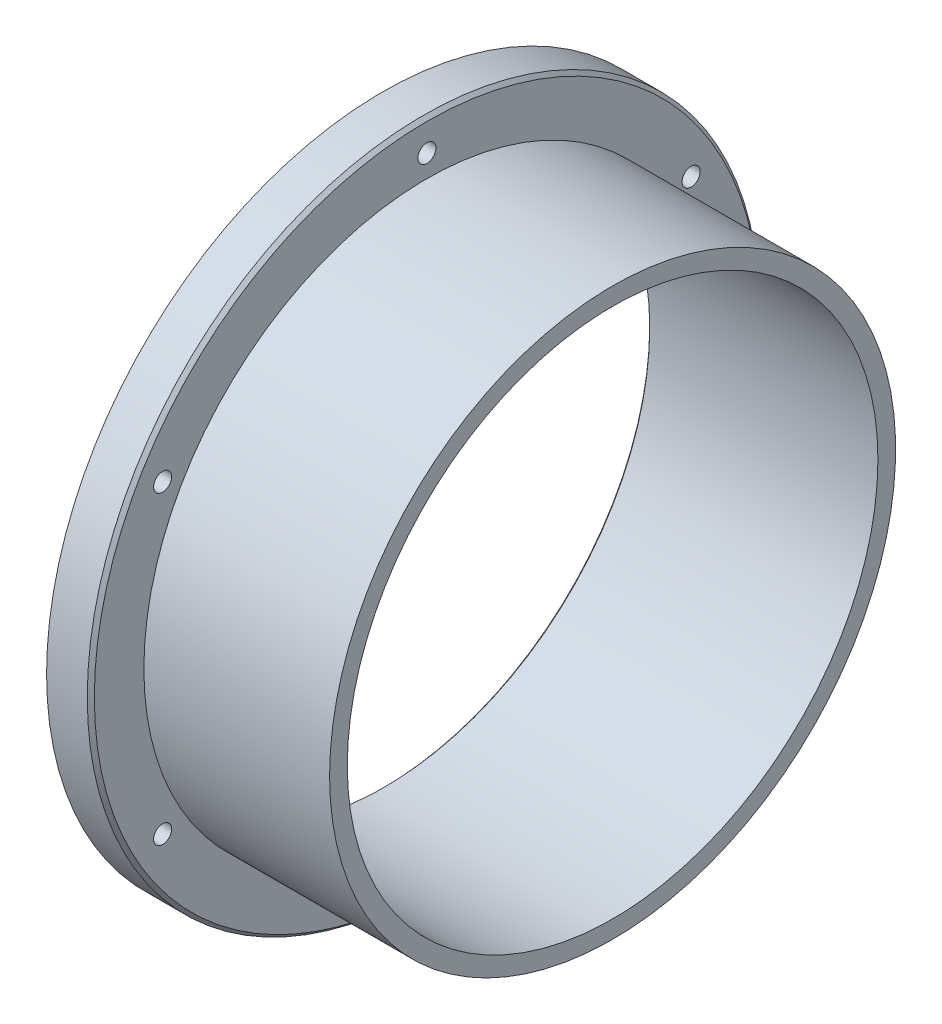
SolidWorks part; units mm, degrees
ref_plane "Спереди" through (0, 0, 0) normal (0, 0, 1) x (1, 0, 0)
ref_plane "Сверху" through (0, 0, 0) normal (0, 1, 0) x (1, 0, 0)
ref_plane "Справа" through (0, 0, 0) normal (1, 0, 0) x (0, 0, -1)
sketch "Эскиз1" plane through (0, 0, 0) normal (0, 0, 1) x (1, 0, 0)
  line L0 (-311.4848, 0) -> (265.4242, 0) construction
  line L1 (-118.0303, 150) -> (11.9697, 150)
  line L2 (11.9697, 150) -> (11.9697, 160)
  line L3 (11.9697, 160) -> (-93.0303, 160)
  line L4 (-93.0303, 160) -> (-93.0303, 190)
  line L5 (-93.0303, 190) -> (-118.0303, 190)
  line L6 (-118.0303, 190) -> (-118.0303, 150)
  dimension "D1" = 380
  dimension "D2" = 300
  dimension "D3" = 320
  dimension "D4" = 130
  dimension "D5" = 105
revolve "Повернуть1" add sketch "Эскиз1" angle 360 about L0
chamfer "Фаска1" distance 2 angle 45 1 edges at (-93.0303, 0, 190)
chamfer "Фаска2" distance 1 angle 45 1 edges at (-118.0303, 0, 150)
sketch "Эскиз2" plane through (-118.0303, 0, 0) normal (-1, 0, 0) x (0, 0, 1)
  line L0 (0, 218.9001) -> (0, -245.901) construction
  circle A0 centre (0, 0) radius 172.5 construction
  circle A1 centre (0, 172.5) radius 8.1754
  dimension "D1" = 345
hole_wizard "Отверстие обработанное метчиком M121" positions "Эскиз5" profile "Эскиз6" tap size "M12" standard "ISO"
sketch "Эскиз5" plane through (-118.0303, 0, 0) normal (-1, 0, 0) x (0, 0, 1)
  point P0 (0, 172.5)
sketch "Эскиз6" plane through (-118.0303, 172.5, 0) normal (0, 1, 0) x (0, 0, 1)
  line L0 (0, 0) -> (0, 35.8144)
  line L1 (0, 35.8144) -> (5.1, 32.75)
  line L2 (5.1, 32.75) -> (5.1, 0)
  line L5 (5.1, 0) -> (0, 0)
  line L10 (0, 35.8144) -> (-5.1, 32.75) construction
  line L11 (0, -6.35) -> (0, 107.95) construction
  dimension "Диаметр сверла" = 10.2
  dimension "Глубина сверла" = 32.75
  dimension "Угол заточки сверла" = 118
cosmetic thread "Отверстие резьбы1" parameters "D1"=24, "D2"=12
pattern_circular "Круговой массив1" count 6 over 360 about axis through (0, 0, 0) along (1, 0, 0) of "Отверстие обработанное метчиком M121"
cosmetic thread "Отверстие резьбы2" parameters "D1"=24, "D2"=12
cosmetic thread "Отверстие резьбы3" parameters "D1"=24, "D2"=12
cosmetic thread "Отверстие резьбы4" parameters "D1"=24, "D2"=12
cosmetic thread "Отверстие резьбы5" parameters "D1"=24, "D2"=12
cosmetic thread "Отверстие резьбы6" parameters "D1"=24, "D2"=12
